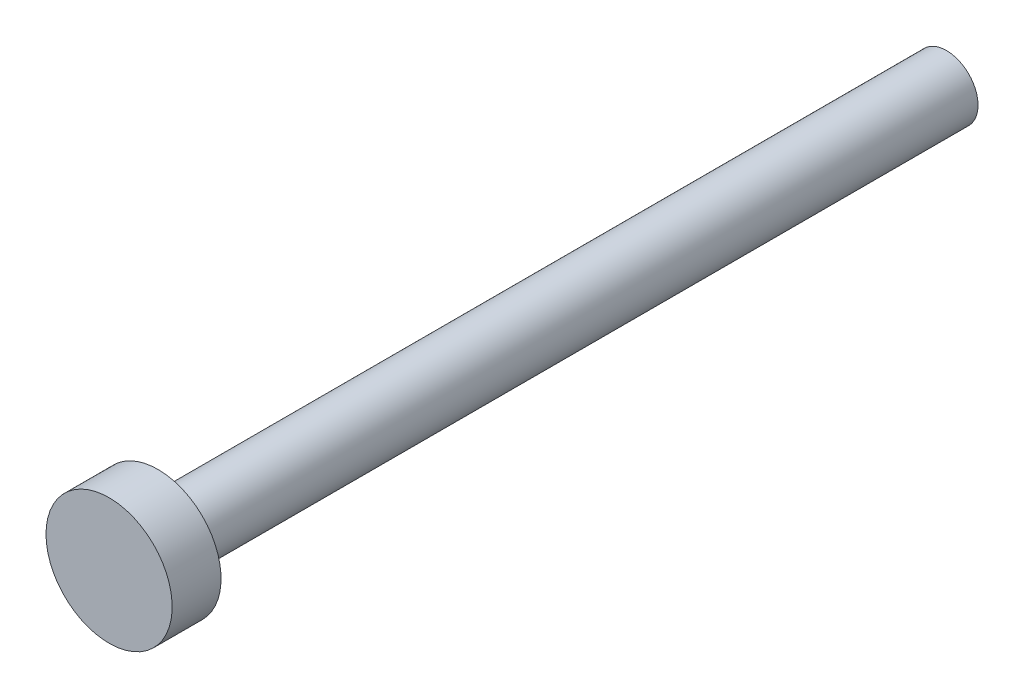
SolidWorks part; units mm, degrees
ref_plane "Plan de face" through (0, 0, 0) normal (0, 0, 1) x (1, 0, 0)
ref_plane "Plan de dessus" through (0, 0, 0) normal (0, 1, 0) x (1, 0, 0)
ref_plane "Plan de droite" through (0, 0, 0) normal (1, 0, 0) x (0, 0, -1)
sketch "Esquisse1" plane through (0, 0, 0) normal (0, 0, 1) x (1, 0, 0)
  circle A0 centre (0, 0) radius 4
  dimension "D1" = 8
extrude "Boss.-Extru.1" add sketch "Esquisse1" along normal blind 3.1
sketch "Esquisse2" plane through (0, 0, 0) normal (0, 0, -1) x (-1, 0, 0)
  circle A0 centre (0, 0) radius 2
  dimension "D1" = 4
extrude "Boss.-Extru.2" add sketch "Esquisse2" along normal blind 50
